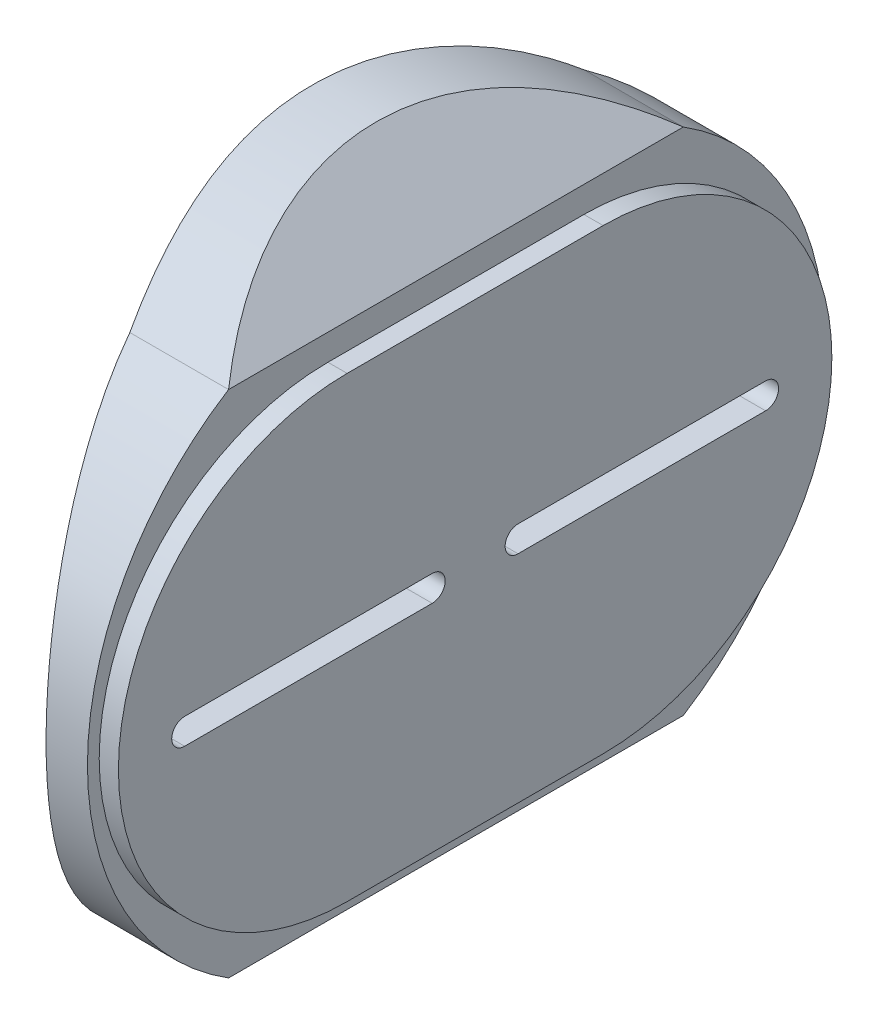
SolidWorks part; units mm, degrees
material "SideBearingMount"
ref_plane "Front Plane" through (0, 0, 0) normal (0, 0, 1) x (1, 0, 0)
ref_plane "Top Plane" through (0, 0, 0) normal (0, 1, 0) x (1, 0, 0)
ref_plane "Right Plane" through (0, 0, 0) normal (1, 0, 0) x (0, 0, -1)
sketch "Sketch1" plane through (0, 0, 0) normal (1, 0, 0) x (0, 0, -1)
  line L0 (-32.65, 0) -> (32.65, 0) construction
  line L1 (-32.65, 58.35) -> (32.65, 58.35)
  line L2 (-32.65, -58.35) -> (32.65, -58.35)
  arc A0 (-32.65, 58.35) -> (-32.65, -58.35) centre (-32.65, 0) ccw
  arc A1 (32.65, -58.35) -> (32.65, 58.35) centre (32.65, 0) ccw
  point P2 (0, 0)
  point P8 (-91, 0)
  point P9 (91, 0)
  dimension "D1" = 182
  dimension "D2" = 116.7
extrude "Boss-Extrude1" add sketch "Sketch1" along normal blind 4.9
sketch "Sketch3" plane through (0, 0, 0) normal (-1, 0, 0) x (0, 0, 1)
  line L0 (-58, 65) -> (58, 65)
  line L1 (-58, -65) -> (58, -65)
  line L2 (-94, -11.2008) -> (-94, 11.2008) construction
  line L3 (94, -15.5829) -> (94, 15.5829) construction
  line L8 (-91, 0) -> (-94, 0)
  line L9 (91, 0) -> (94, 0)
  arc A0 (-32.65, 58.35) -> (-32.65, -58.35) centre (-32.65, 0) ccw construction
  arc A1 (32.65, -58.35) -> (32.65, 58.35) centre (32.65, 0) ccw construction
  arc A2 (-58, -65) -> (-58, 65) centre (-17.3194, 0) cw
  arc A3 (58, -65) -> (58, 65) centre (17.3194, 0) ccw
  point P4 (0, 65)
  point P5 (0, -65)
  point P13 (-91, 0)
  point P21 (-94, 0)
  point P25 (94, 0)
  dimension "D1" = 130
  dimension "D2" = 65
  dimension "D3" = 116
  dimension "D4" = 116
  dimension "D5" = 3
  dimension "D6" = 3
extrude "Boss-Extrude2" add sketch "Sketch3" along normal blind 35 contours A3 L0 A2 L1
sketch "Sketch2" plane through (4.9, 0, 0) normal (1, 0, 0) x (0, 0, -1)
  line L0 (-10.95, 0) -> (-74.1, 0) construction
  line L1 (-10.95, -3.3) -> (-74.1, -3.3)
  line L2 (-10.95, 3.3) -> (-74.1, 3.3)
  line L3 (10.95, 0) -> (74.1, 0) construction
  line L4 (10.95, 3.3) -> (74.1, 3.3)
  line L5 (10.95, -3.3) -> (74.1, -3.3)
  arc A0 (-10.95, -3.3) -> (-10.95, 3.3) centre (-10.95, 0) ccw
  arc A1 (-74.1, 3.3) -> (-74.1, -3.3) centre (-74.1, 0) ccw
  arc A2 (10.95, 3.3) -> (10.95, -3.3) centre (10.95, 0) ccw
  arc A3 (74.1, -3.3) -> (74.1, 3.3) centre (74.1, 0) ccw
  point P3 (-42.525, 0)
  point P8 (42.525, 0)
  point P15 (-7.65, 0)
  point P16 (7.65, 0)
  point P17 (-77.4, 0)
  point P18 (77.4, 0)
  dimension "D1" = 15.3
  dimension "D2" = 6.6
  dimension "D3" = 6.6
  dimension "D4" = 69.75
  dimension "D5" = 69.75
  dimension "D6" = 7.65
extrude "Cut-Extrude1" cut sketch "Sketch2" against normal through all
ref_plane "Plane1" through (0, 0, -94) normal (0, 0, -1) x (-1, 0, 0)
ref_plane "Plane2" through (0, -65, -58) normal (1, 0, 0) x (0, 0, -1)
sketch "Sketch5" plane through (0, -65, -58) normal (1, 0, 0) x (0, 0, -1)
  line L0 (0, 130) -> (-116, 130) construction
  line L1 (0, 0) -> (-116, 0) construction
  line L2 (-116, 0) -> (0, 0)
  line L3 (-116, 130) -> (0, 130)
  arc A0 (-116, 130) -> (0, 130) centre (-58, 55.9) cw
  arc A1 (0, 0) -> (-116, 0) centre (-58, 74.1) cw
  point P3 (-58, 150)
  point P11 (-58, -20)
  point P16 (-58, 0)
  dimension "D1" = 20
  dimension "D2" = 20
extrude "Boss-Extrude3" add sketch "Sketch5" against normal blind 40
sketch "Sketch4" plane through (0, 0, -94) normal (0, 0, -1) x (-1, 0, 0)
  line L0 (10.55, -25.216) -> (10.55, 25.216) construction
  line L1 (0, 65) -> (0, -65) construction
  circle A0 centre (162.1451, 0) radius 151.5951
  point P3 (10.55, 0)
  point P5 (0, 0)
  dimension "D2" = 303.1902
  dimension "D1" = 10.55
extrude "Cut-Extrude2" cut sketch "Sketch4" against normal through all
sketch "Sketch8" plane through (0, 0, -94) normal (0, 0, -1) x (-1, 0, 0)
  line L0 (0, 65) -> (0, 85)
  line L1 (0, 85) -> (0, 65) construction
  line L2 (36.6219, 85) -> (0, 85) construction
  line L3 (0, 85) -> (20.3219, 85)
  line L4 (20.3219, 85) -> (0, 65)
  line L5 (0, -65) -> (0, -85)
  line L6 (25.1923, -65) -> (0, -65) construction
  line L7 (0, -10) -> (0, -120) construction
  line L8 (0, -85) -> (36.6219, -85) construction
  line L9 (0, -85) -> (20.3219, -85)
  line L10 (20.3219, -85) -> (0, -65)
  dimension "D1" = 16.3
  dimension "D2" = 16.3
extrude "Cut-Extrude3" cut sketch "Sketch8" against normal through all
